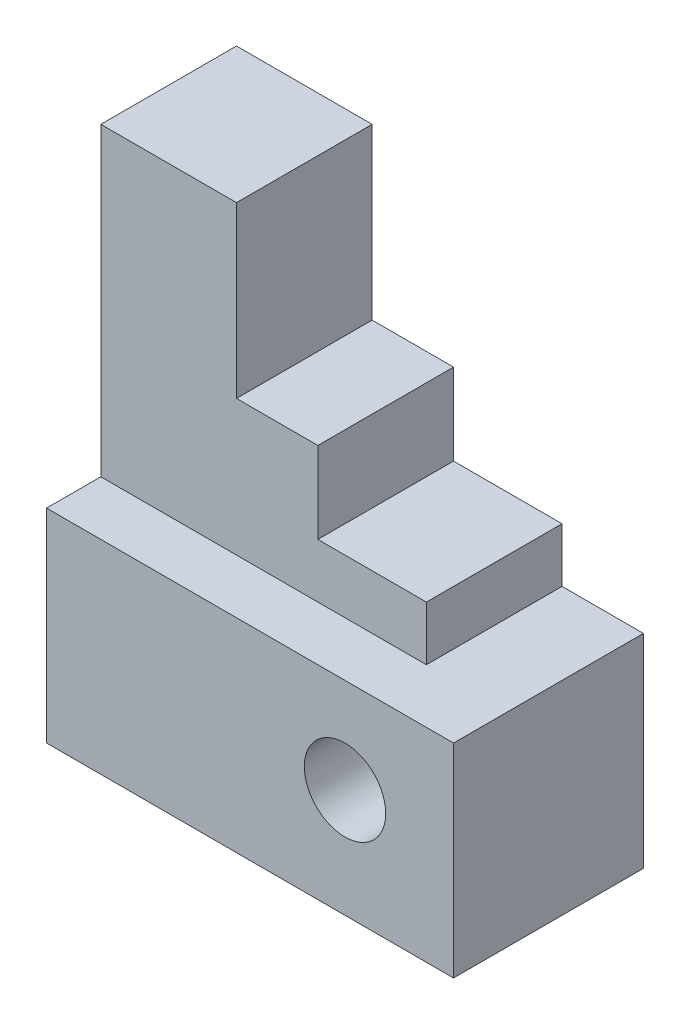
SolidWorks part; units mm, degrees
ref_plane "Front Plane" through (0, 0, 0) normal (0, 0, 1) x (1, 0, 0)
ref_plane "Top Plane" through (0, 0, 0) normal (0, 1, 0) x (1, 0, 0)
ref_plane "Right Plane" through (0, 0, 0) normal (1, 0, 0) x (0, 0, -1)
sketch "Sketch1" plane through (0, 0, 0) normal (0, 1, 0) x (1, 0, 0)
  line L0 (-30, 0) -> (30, 0)
  line L1 (30, 0) -> (30, 28)
  line L2 (30, 28) -> (-30, 28)
  line L3 (-30, 28) -> (-30, 0)
  point P4 (0, 0)
  dimension "D1" = 60
  dimension "D2" = 28
extrude "Boss-Extrude1" add sketch "Sketch1" along normal blind 30
sketch "Sketch2" plane through (0, 30, 0) normal (0, 1, 0) x (1, 0, 0)
  line L0 (-30, 8) -> (18, 8)
  line L1 (-30, 28) -> (-30, 0) construction
  line L2 (18, 8) -> (18, 28)
  line L3 (30, 28) -> (-30, 28) construction
  line L4 (18, 28) -> (-30, 28)
  line L5 (-30, 28) -> (-30, 8)
  dimension "D1" = 20
  dimension "D2" = 48
extrude "Boss-Extrude2" add sketch "Sketch2" along normal blind 8
sketch "Sketch3" plane through (0, 38, 0) normal (0, 1, 0) x (1, 0, 0)
  line L0 (2, 28) -> (2, 8)
  line L1 (18, 28) -> (-30, 28) construction
  line L2 (-30, 8) -> (18, 8) construction
  line L3 (2, 8) -> (-30, 8)
  line L4 (-30, 8) -> (-30, 28)
  line L5 (-30, 28) -> (2, 28)
  dimension "D1" = 32
extrude "Boss-Extrude3" add sketch "Sketch3" along normal blind 12
sketch "Sketch4" plane through (0, 50, 0) normal (0, 1, 0) x (1, 0, 0)
  line L0 (-10, 28) -> (-10, 8)
  line L1 (2, 28) -> (-30, 28) construction
  line L2 (-30, 8) -> (18, 8) construction
  line L3 (-10, 8) -> (-30, 8)
  line L4 (-30, 8) -> (-30, 28)
  line L5 (-30, 28) -> (-10, 28)
  dimension "D1" = 20
extrude "Boss-Extrude4" add sketch "Sketch4" along normal blind 25
sketch "Sketch5" plane through (0, 0, 0) normal (0, 0, 1) x (1, 0, 0)
  line L0 (30, 30) -> (30, 0) construction
  line L5 (-30, 0) -> (30, 0) construction
  circle A1 centre (14, 16) radius 6
  point P0 (14, 16)
  dimension "D3" = 12
  dimension "D1" = 16
  dimension "D2" = 16
extrude "Cut-Extrude1" cut sketch "Sketch5" against normal through all
